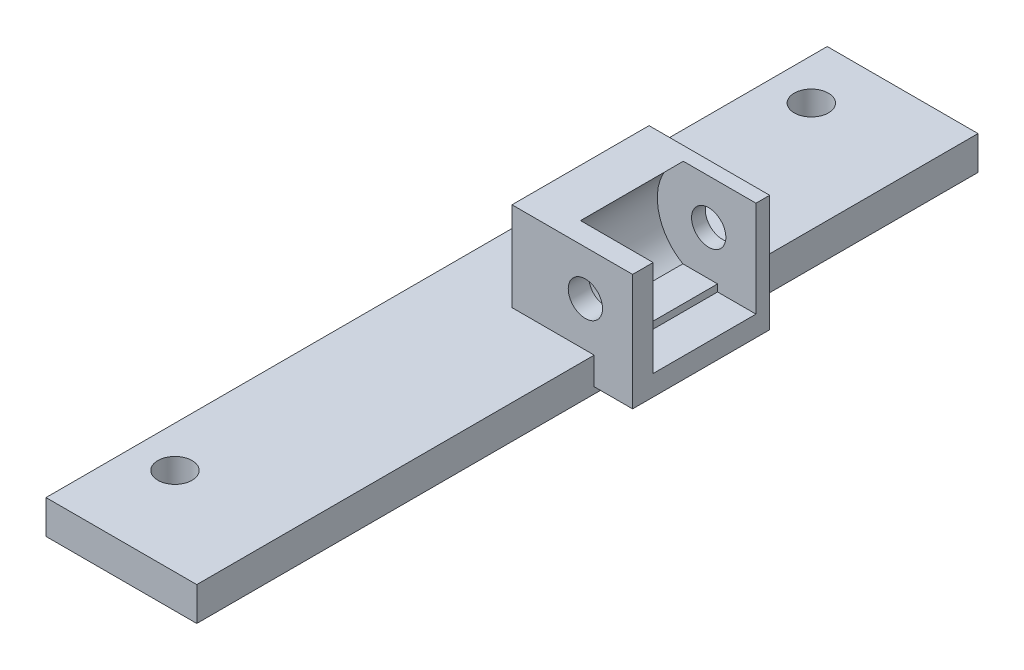
SolidWorks part; units mm, degrees
ref_plane "Front Plane" through (0, 0, 0) normal (0, 0, 1) x (1, 0, 0)
ref_plane "Top Plane" through (0, 0, 0) normal (0, 1, 0) x (1, 0, 0)
ref_plane "Right Plane" through (0, 0, 0) normal (1, 0, 0) x (0, 0, -1)
sketch "Sketch1" plane through (0, 0, 0) normal (0, 0, 1) x (1, 0, 0)
  line L0 (-792.5838, 96.1608) -> (-801.3383, 96.1608)
  line L1 (-814.9358, 113.9662) -> (-792.5838, 113.9662)
  line L2 (-814.9358, 113.9662) -> (-814.9358, 92.3762)
  line L3 (-814.9358, 92.3762) -> (-792.5838, 92.3762)
  line L4 (-792.5838, 113.9662) -> (-792.5838, 92.3762)
  circle A0 centre (-801.3383, 105.6858) radius 3.175
  arc A1 (-801.3383, 96.1608) -> (-806.0458, 97.4054) centre (-801.3383, 105.6858) cw
  arc A2 (-806.0458, 97.4054) -> (-806.0458, 113.9662) centre (-801.3383, 105.6858) cw
  dimension "D1" = 6.35
extrude "Boss-Extrude1" add sketch "Sketch1" against normal blind 21.59 contours A1 A2 L1 L2 L3 L4 L0
sketch "Sketch2" plane through (0, 0, 0) normal (0, 0, 1) x (1, 0, 0)
  line L1 (-814.9358, 92.3762) -> (-792.5838, 92.3762)
  line L2 (-814.9358, 92.3762) -> (-814.9358, 113.9662)
  line L3 (-814.9358, 113.9662) -> (-792.5838, 113.9662)
  line L4 (-792.5838, 92.3762) -> (-792.5838, 113.9662)
  circle A0 centre (-801.3383, 105.6858) radius 3.175
  dimension "D1" = 6.35
extrude "Boss-Extrude2" add sketch "Sketch2" along normal blind 3.81
sketch "Sketch3" plane through (0, 0, -21.59) normal (0, 0, -1) x (-1, 0, 0)
  line L0 (792.5838, 96.1608) -> (801.3383, 96.1608)
  line L1 (792.5838, 92.3762) -> (814.9358, 92.3762)
  line L2 (792.5838, 92.3762) -> (792.5838, 113.9662)
  line L3 (792.5838, 113.9662) -> (814.9358, 113.9662)
  line L4 (814.9358, 92.3762) -> (814.9358, 113.9662)
  circle A0 centre (801.3383, 105.6858) radius 3.175
  arc A1 (801.3383, 96.1608) -> (806.0458, 113.9662) centre (801.3383, 105.6858) ccw
  arc M5 (806.0458, 113.9662) -> (801.3383, 96.1608) centre (801.3383, 105.6858) cw
  line M6 (801.3383, 96.1608) -> (792.5838, 96.1608)
  dimension "D1" = 6.35
extrude "Boss-Extrude3" add sketch "Sketch3" against normal up to surface (2.54 mm away) contours L3 L2 A0 M6 M5
sketch "Sketch4" plane through (0, 92.3762, 0) normal (0, -1, 0) x (1, 0, 0)
  line L1 (-799.6958, -67.31) -> (-827.6358, -67.31)
  line L2 (-799.6958, -67.31) -> (-799.6958, 77.47)
  line L3 (-799.6958, 77.47) -> (-827.6358, 77.47)
  line L4 (-827.6358, -67.31) -> (-827.6358, 77.47)
  circle A0 centre (-820.039, -56.7657) radius 3.175
  circle A1 centre (-820.039, 61.1629) radius 3.175
  dimension "D1" = 6.35
  dimension "D2" = 6.35
extrude "Boss-Extrude4" add sketch "Sketch4" along normal up to surface (1.1648 mm away) and the other way blind 5.08
